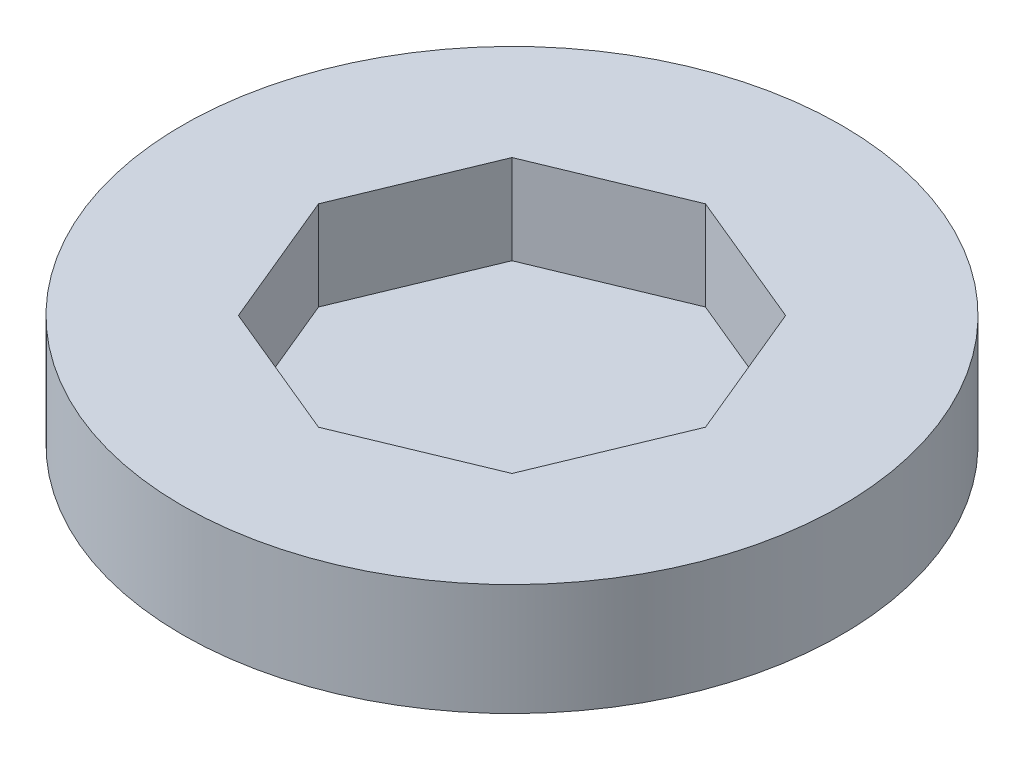
SolidWorks part; units mm, degrees
ref_plane "Front Plane" through (0, 0, 0) normal (0, 0, 1) x (1, 0, 0)
ref_plane "Top Plane" through (0, 0, 0) normal (0, 1, 0) x (1, 0, 0)
ref_plane "Right Plane" through (0, 0, 0) normal (1, 0, 0) x (0, 0, -1)
sketch "Sketch1" plane through (0, 0, 0) normal (0, 1, 0) x (1, 0, 0)
  circle A0 centre (0, 0) radius 29.5
extrude "Boss-Extrude1" add sketch "Sketch1" along normal blind 10
sketch "Sketch2" plane through (0, 10, 0) normal (0, 1, 0) x (1, 0, 0)
  line L1 (12.2459, 12.2459) -> (0, 17.3183)
  line L2 (0, 17.3183) -> (-12.2459, 12.2459)
  line L3 (-12.2459, 12.2459) -> (-17.3183, 0)
  line L4 (-17.3183, 0) -> (-12.2459, -12.2459)
  line L5 (-12.2459, -12.2459) -> (0, -17.3183)
  line L6 (0, -17.3183) -> (12.2459, -12.2459)
  line L7 (12.2459, -12.2459) -> (17.3183, 0)
  line L8 (17.3183, 0) -> (12.2459, 12.2459)
  circle A0 centre (0, 0) radius 16 construction
extrude "Cut-Extrude1" cut sketch "Sketch2" against normal blind 8
